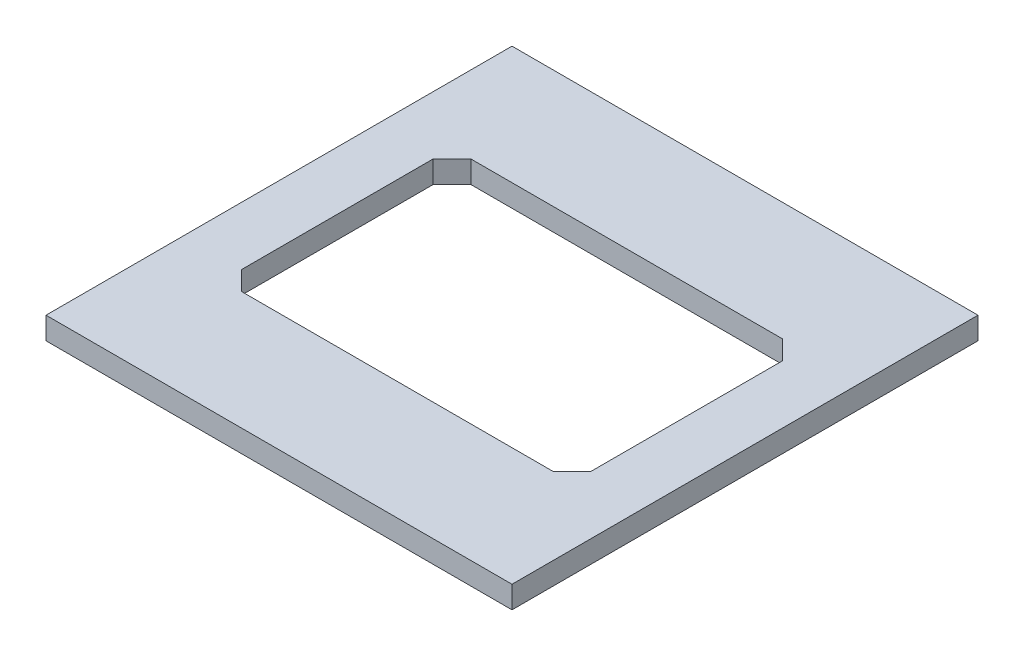
SolidWorks part; units mm, degrees
ref_plane "Front Plane" through (0, 0, 0) normal (0, 0, 1) x (1, 0, 0)
ref_plane "Top Plane" through (0, 0, 0) normal (0, 1, 0) x (1, 0, 0)
ref_plane "Right Plane" through (0, 0, 0) normal (1, 0, 0) x (0, 0, -1)
sketch "Sketch1" plane through (0, 0, 0) normal (0, 1, 0) x (1, 0, 0)
  line L0 (0, 200) -> (0, -200) construction
  line L1 (-200, 0) -> (200, 0) construction
  line L3 (-200, 200) -> (200, 200)
  line L4 (-200, 200) -> (-200, -200)
  line L5 (-200, -200) -> (200, -200)
  line L6 (200, 200) -> (200, -200)
  point P5 (0, 0)
  point P10 (0, 0)
  point P11 (0, 0)
  point P12 (0, 0)
  dimension "D1" = 400
extrude "Boss-Extrude1" add sketch "Sketch1" along normal blind 19.05
sketch "Sketch2" plane through (0, 19.05, 0) normal (0, 1, 0) x (1, 0, 0)
  line L0 (-150, -82.2365) -> (-150, 82.2365)
  line L1 (-150, 82.2365) -> (-133.7365, 98.5)
  line L2 (-133.7365, 98.5) -> (133.7365, 98.5)
  line L3 (133.7365, 98.5) -> (150, 82.2365)
  line L4 (150, 82.2365) -> (150, -82.2365)
  line L5 (150, -82.2365) -> (133.7365, -98.5)
  line L6 (133.7365, -98.5) -> (-133.7365, -98.5)
  line L7 (-133.7365, -98.5) -> (-150, -82.2365)
  line L8 (0, 200) -> (0, -200) construction
  line L9 (200, 200) -> (-200, 200) construction
  line L10 (-200, -200) -> (200, -200) construction
  line L11 (-200, 0) -> (200, 0) construction
  line L12 (-200, 200) -> (-200, -200) construction
  line L13 (200, -200) -> (200, 200) construction
  point P2 (0, 0)
  point P9 (0, 0)
  dimension "D1" = 300
  dimension "D2" = 197
  dimension "D3" = 23
extrude "Cut-Extrude1" cut sketch "Sketch2" against normal through all
